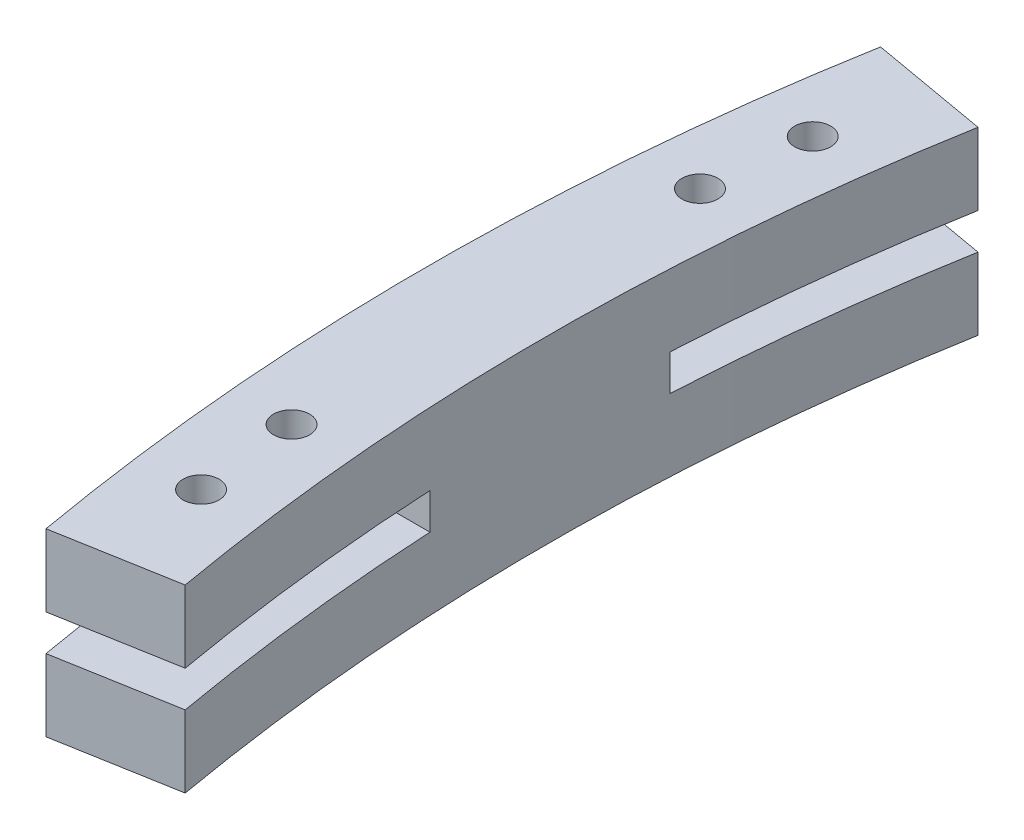
SolidWorks part; units mm, degrees
ref_plane "Front Plane" through (0, 0, 0) normal (0, 0, 1) x (1, 0, 0)
ref_plane "Top Plane" through (0, 0, 0) normal (0, 1, 0) x (1, 0, 0)
ref_plane "Right Plane" through (0, 0, 0) normal (1, 0, 0) x (0, 0, -1)
sketch "Sketch1" plane through (0, 0, 0) normal (0, 0, 1) x (1, 0, 0)
  line L0 (190, 0) -> (-190, 0) construction
  line L1 (0, 190) -> (0, -190) construction
  line L2 (0, 0) -> (-187.1135, 32.9932) construction
  line L3 (0, 0) -> (-187.1135, -32.9932) construction
  line L4 (-187.1135, 32.9932) -> (-196.9616, 34.7296)
  line L5 (-187.1135, -32.9932) -> (-196.9616, -34.7296)
  arc A0 (-187.1135, 32.9932) -> (-187.1135, -32.9932) centre (0, 0) ccw
  arc A1 (-196.9616, 34.7296) -> (-196.9616, -34.7296) centre (0, 0) ccw
  circle A3 centre (0, 0) radius 190 construction
  dimension "D1" = 380
  dimension "D2" = 10
  dimension "D3" = 20
sketch "Sketch9" plane through (0, 0, 0) normal (0, 1, 0) x (1, 0, 0)
  line L0 (0, 0) -> (-196.9616, 34.7296)
  line L1 (-200, 0) -> (200, 0) construction
  line L2 (0, 0) -> (-196.9616, -34.7296)
  circle A0 centre (0, 0) radius 195 construction
  circle A1 centre (0, 0) radius 195 construction
  circle A8 centre (0, 0) radius 200 construction
  circle A9 centre (0, 0) radius 190 construction
  circle A10 centre (0, 0) radius 200
  circle A11 centre (0, 0) radius 190
  dimension "D1" = 20
extrude "base" add sketch "Sketch9" along normal mid plane 15 contours A11 L0 A10 L2
sketch "Sketch11" plane through (0, 0, 0) normal (0, 1, 0) x (1, 0, 0)
  line L8 (-189.7367, -10) -> (-199.7498, -10) construction
  line L9 (-187.1135, -32.9932) -> (-196.9616, -34.7296) construction
  line L10 (-189.7367, 10) -> (-199.7498, 10) construction
  line L11 (-187.1135, 32.9932) -> (-196.9616, 34.7296) construction
  line L12 (-189.7367, -10) -> (-199.7498, -10)
  line L13 (-187.1135, -32.9932) -> (-196.9616, -34.7296)
  line L14 (-189.7367, 10) -> (-199.7498, 10)
  line L15 (-187.1135, 32.9932) -> (-196.9616, 34.7296)
  circle A14 centre (0, 0) radius 200 construction
  circle A15 centre (0, 0) radius 190 construction
  arc A16 (-196.9616, 34.7296) -> (-199.7498, 10) centre (0, 0) ccw
  arc A17 (-187.1135, 32.9932) -> (-189.7367, 10) centre (0, 0) ccw
  arc A18 (-199.7498, -10) -> (-196.9616, -34.7296) centre (0, 0) ccw
  arc A19 (-189.7367, -10) -> (-187.1135, -32.9932) centre (0, 0) ccw
extrude "mount" cut sketch "Sketch11" along normal up to surface and the other way up to surface
sketch "Sketch12" plane through (0, 0, 0) normal (0, 1, 0) x (1, 0, 0)
  line L0 (-200, 0) -> (200, 0) construction
  line L1 (-200, 0) -> (200, 0) construction
  line L2 (0, 0) -> (-193.3317, 25.4526) construction
  line L3 (0, 0) -> (-194.258, 16.9954) construction
  line L4 (0, 0) -> (-194.258, -16.9954) construction
  line L5 (0, 0) -> (-193.3317, -25.4526) construction
  circle A0 centre (0, 0) radius 195 construction
  circle A1 centre (0, 0) radius 195 construction
  circle A2 centre (-193.3317, 25.4526) radius 1.5
  circle A3 centre (-194.258, 16.9954) radius 1.5
  circle A4 centre (-194.258, -16.9954) radius 1.5
  circle A5 centre (-193.3317, -25.4526) radius 1.5
  dimension "D1" = 3
  dimension "D2" = 10
  dimension "D3" = 15
extrude "mount hole" cut sketch "Sketch12" against normal through all both and the other way through all
sketch "Sketch13" plane through (0, 0, 0) normal (0, 1, 0) x (1, 0, 0)
  line L0 (0, 0) -> (-195, 0) construction
  line L1 (-200, 0) -> (200, 0) construction
  line L2 (-195, 0) -> (-197.5, 0)
  line L18 (-197.5, 0) -> (-197.5, 3.5)
  line L19 (-197.5, 3.5) -> (-195, 3.5)
  line L20 (-195, 0) -> (-195, 3.5)
  circle A0 centre (0, 0) radius 195 construction
  dimension "D1" = 2.5
  dimension "D2" = 7
ref_plane "shaft" through (-195, 0, 0) normal (-1, 0, 0) x (0, 0, 1)
sketch "Sketch14" plane through (-195, 0, 0) normal (-1, 0, 0) x (0, 0, 1)
  circle A0 centre (0, 0) radius 2
  dimension "D1" = 4
extrude "shaft hole" cut sketch "Sketch14" along normal through all
revolve "bearinghole" cut sketch "Sketch13" angle 360 about L0
